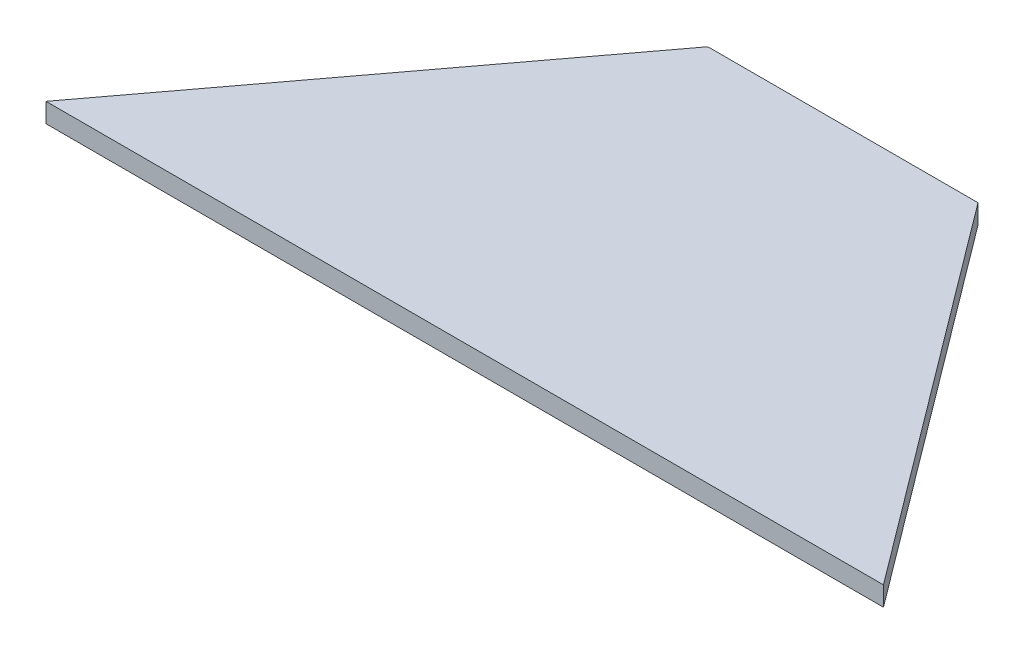
SolidWorks part; units mm, degrees
material "Pine"
ref_plane "Front Plane" through (0, 0, 0) normal (0, 0, 1) x (1, 0, 0)
ref_plane "Top Plane" through (0, 0, 0) normal (0, 1, 0) x (1, 0, 0)
ref_plane "Right Plane" through (0, 0, 0) normal (1, 0, 0) x (0, 0, -1)
sketch "Sketch1" plane through (0, 0, 0) normal (0, 1, 0) x (1, 0, 0)
  line L0 (393.7, 0) -> (-393.7, 0)
  line L1 (-393.7, 0) -> (-127, 355.6)
  line L2 (-127, 355.6) -> (127, 355.6)
  line L3 (127, 355.6) -> (393.7, 0)
  point P4 (0, 0)
  point P7 (0, 355.6)
  dimension "D1" = 254
  dimension "D2" = 355.6
  dimension "D3" = 787.4
extrude "Boss-Extrude1" add sketch "Sketch1" along normal blind 18.2562
